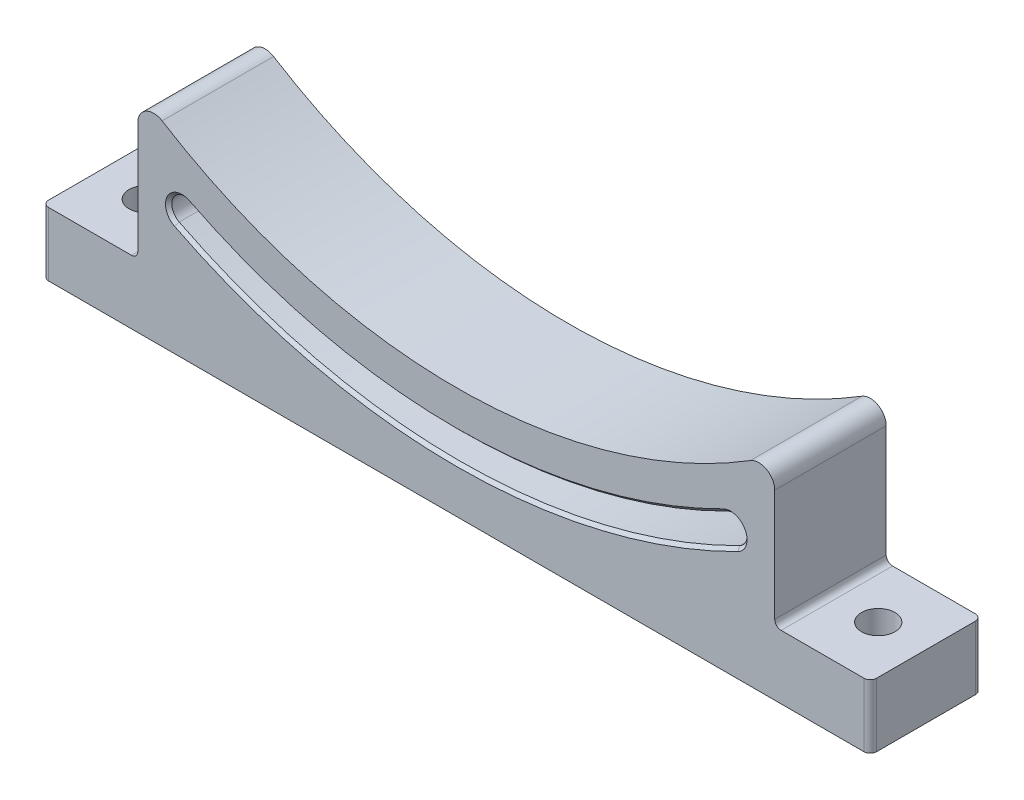
SolidWorks part; units mm, degrees
material "Alumina"
ref_plane "Front Plane" through (0, 0, 0) normal (0, 0, 1) x (1, 0, 0)
ref_plane "Top Plane" through (0, 0, 0) normal (0, 1, 0) x (1, 0, 0)
ref_plane "Right Plane" through (0, 0, 0) normal (1, 0, 0) x (0, 0, -1)
sketch "Sketch1" plane through (0, 0, 0) normal (0, 0, 1) x (1, 0, 0)
  line L0 (0, 0) -> (-200, 0)
  line L1 (-200, 0) -> (-200, 66.3859)
  line L2 (0, 0) -> (0, 66.3859)
  line L3 (-100, 0) -> (-100, 210) construction
  line L4 (-200, 66.3859) -> (-200, 53.3859) construction
  line L5 (-200, 53.3859) -> (-200, 33.9728) construction
  line L6 (-200, 53.3859) -> (-200, 38.6603) construction
  arc A0 (-200, 66.3859) -> (0, 66.3859) centre (-100, 210) ccw
  arc A1 (-184.217, 43.0374) -> (-15.783, 43.0374) centre (-100, 210) ccw
  arc A2 (-188, 35.5375) -> (-12, 35.5375) centre (-100, 210) ccw
  arc A3 (-189.8375, 41.22) -> (-10.1625, 41.22) centre (-100, 210) ccw construction
  arc A4 (-184.217, 43.0374) -> (-188, 35.5375) centre (-186.1085, 39.2875) ccw
  arc A5 (-15.783, 43.0374) -> (-12, 35.5375) centre (-13.8915, 39.2875) cw
  point P3 (-100, 35)
  point P13 (-100, 23)
  dimension "D3" = 175
  dimension "D9" = 4.2
  dimension "D6" = 4.2
  dimension "D7" = 4.2
  dimension "D13" = 4.2
  dimension "D1" = 200
  dimension "D2" = 210
  dimension "D4" = 35
  dimension "D5" = 13
  dimension "D8" = 12
  dimension "D11" = 12
extrude "Boss-Extrude1" add sketch "Sketch1" along normal blind 35
fillet "Fillet1" radius 5 2 edges at (0, 66.3859, 17.5) (-200, 66.3859, 17.5)
chamfer "Chamfer1" distance 1 angle 45 8 edges at (-100, 14.6, 35) (-10.1415, 41.179, 35) (-189.8585, 41.179, 35) (-100, 23, 35) (-100, 14.6, 0) (-10.1415, 41.179, 0) (-189.8585, 41.179, 0) (-100, 23, 0)
sketch "Sketch2" plane through (0, 0, 0) normal (1, 0, 0) x (0, 0, -1)
  line L0 (-35, 0) -> (-35, 57.1112) construction
  line L1 (-35, 20) -> (0, 20)
  line L2 (-35, 20) -> (-35, 0)
  line L3 (-35, 0) -> (0, 0)
  line L4 (0, 20) -> (0, 0)
  dimension "D1" = 20
extrude "Boss-Extrude2" add sketch "Sketch2" along normal blind 30
fillet "Fillet2" radius 2 1 edges at (0, 20, 17.5)
sketch "Sketch3" plane through (-200, 0, 0) normal (-1, 0, 0) x (0, 0, 1)
  line L0 (0, 57.1112) -> (0, 0) construction
  line L1 (0, 20) -> (35, 20)
  line L2 (0, 20) -> (0, 0)
  line L3 (0, 0) -> (35, 0)
  line L4 (35, 20) -> (35, 0)
  dimension "D1" = 20
extrude "Boss-Extrude3" add sketch "Sketch3" along normal blind 30
fillet "Fillet3" radius 2 1 edges at (-200, 20, 17.5)
fillet "Fillet4" radius 2 4 edges at (30, 10, 35) (30, 10, 0) (-230, 10, 35) (-230, 10, 0)
sketch "Sketch4" plane through (0, 20, 0) normal (0, 1, 0) x (1, 0, 0)
  line L0 (-215, 0) -> (-215, -35) construction
  line L1 (-228, 0) -> (-202, 0) construction
  line L2 (-228, -35) -> (-202, -35) construction
  line L3 (-100, 0) -> (-100, -35) construction
  line L4 (-7.6389, 0) -> (-192.3611, 0) construction
  line L5 (-192.3611, -35) -> (-7.6389, -35) construction
  circle A0 centre (-215, -17.5) radius 5.25
  circle A1 centre (15, -17.5) radius 5.25
  dimension "D1" = 10.5
extrude "Cut-Extrude1" cut sketch "Sketch4" against normal up to surface (20 mm away) up to face at (-100, 0, 17.5)
